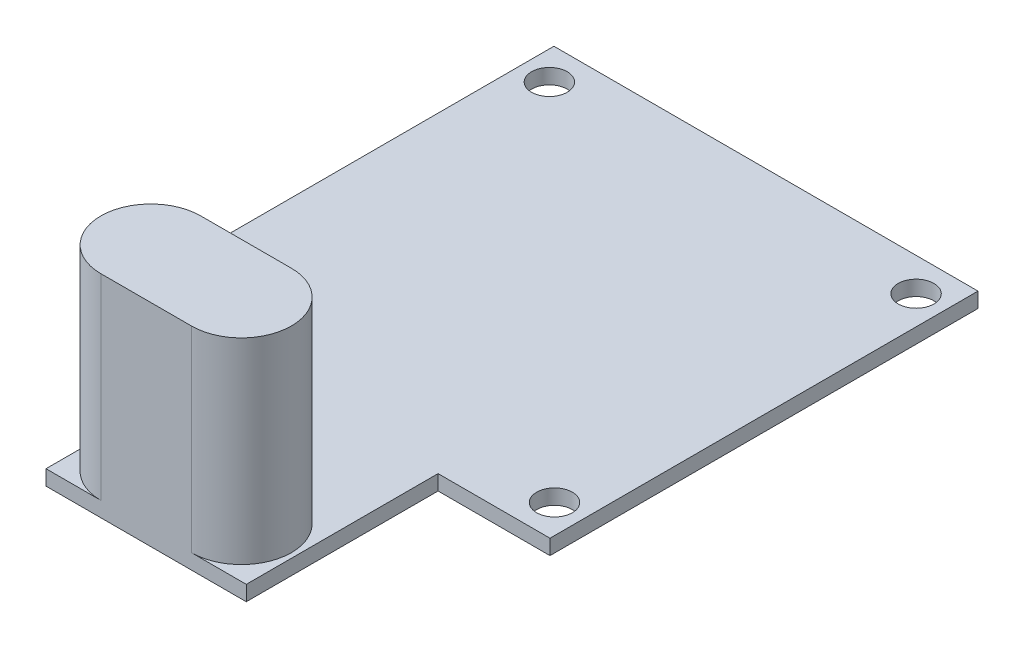
SolidWorks part; units mm, degrees
material "Silicon"
ref_plane "Front Plane" through (0, 0, 0) normal (0, 0, 1) x (1, 0, 0)
ref_plane "Top Plane" through (0, 0, 0) normal (0, 1, 0) x (1, 0, 0)
ref_plane "Right Plane" through (0, 0, 0) normal (1, 0, 0) x (0, 0, -1)
sketch "Sketch1" plane through (0, 0, 0) normal (0, 1, 0) x (1, 0, 0)
  line L0 (17.8308, 35.9918) -> (17.8308, -16.129) construction
  line L1 (0, 0) -> (9.4107, 0)
  line L2 (0, 0) -> (0, 35.9918)
  line L3 (0, 35.9918) -> (35.6616, 35.9918)
  line L4 (35.6616, 0) -> (35.6616, 35.9918)
  line L6 (9.4107, 0) -> (9.4107, -16.129)
  line L7 (9.4107, -16.129) -> (26.2509, -16.129)
  line L8 (26.2509, 0) -> (26.2509, -16.129)
  line L9 (26.2509, 0) -> (35.6616, 0)
  dimension "D1" = 35.9918
  dimension "D2" = 35.6616
  dimension "D3" = 16.8402
  dimension "D4" = 52.1208
extrude "Boss-Extrude1" add sketch "Sketch1" along normal mid plane 1.27
sketch "Sketch2" plane through (0, 0.635, 0) normal (0, 1, 0) x (1, 0, 0)
  line L0 (17.8308, 35.9918) -> (17.8308, -16.129) construction
  line L1 (35.6616, 35.9918) -> (0, 35.9918) construction
  line L2 (9.4107, -16.129) -> (26.2509, -16.129) construction
  line L3 (14.0208, -11.9253) -> (21.6408, -11.9253) construction
  line L4 (14.0208, -7.7216) -> (21.6408, -7.7216)
  line L5 (14.0208, -16.129) -> (21.6408, -16.129)
  arc A0 (14.0208, -7.7216) -> (14.0208, -16.129) centre (14.0208, -11.9253) ccw
  arc A1 (21.6408, -16.129) -> (21.6408, -7.7216) centre (21.6408, -11.9253) ccw
  point P8 (17.8308, -11.9253)
  dimension "D2" = 7.62
  dimension "D1" = 8.4074
extrude "Boss-Extrude2" add sketch "Sketch2" along normal blind 16.51
sketch "Sketch3" plane through (0, 0.635, 0) normal (0, 1, 0) x (1, 0, 0)
  line L0 (35.6616, 35.9918) -> (0, 35.9918) construction
  line L1 (0, 35.9918) -> (0, 0) construction
  line L2 (0, 17.9959) -> (35.6616, 17.9959) construction
  line L3 (35.6616, 0) -> (35.6616, 35.9918) construction
  line L4 (17.8308, 35.9918) -> (17.8308, 0) construction
  circle A0 centre (2.413, 33.1978) radius 1.4999
  circle A1 centre (2.413, 2.794) radius 1.4999
  circle A2 centre (33.2486, 2.794) radius 1.4999
  circle A3 centre (33.2486, 33.1978) radius 1.4999
  dimension "D1" = 2.9997
  dimension "D2" = 2.794
  dimension "D3" = 2.413
extrude "Cut-Extrude2" cut sketch "Sketch3" against normal up to next
